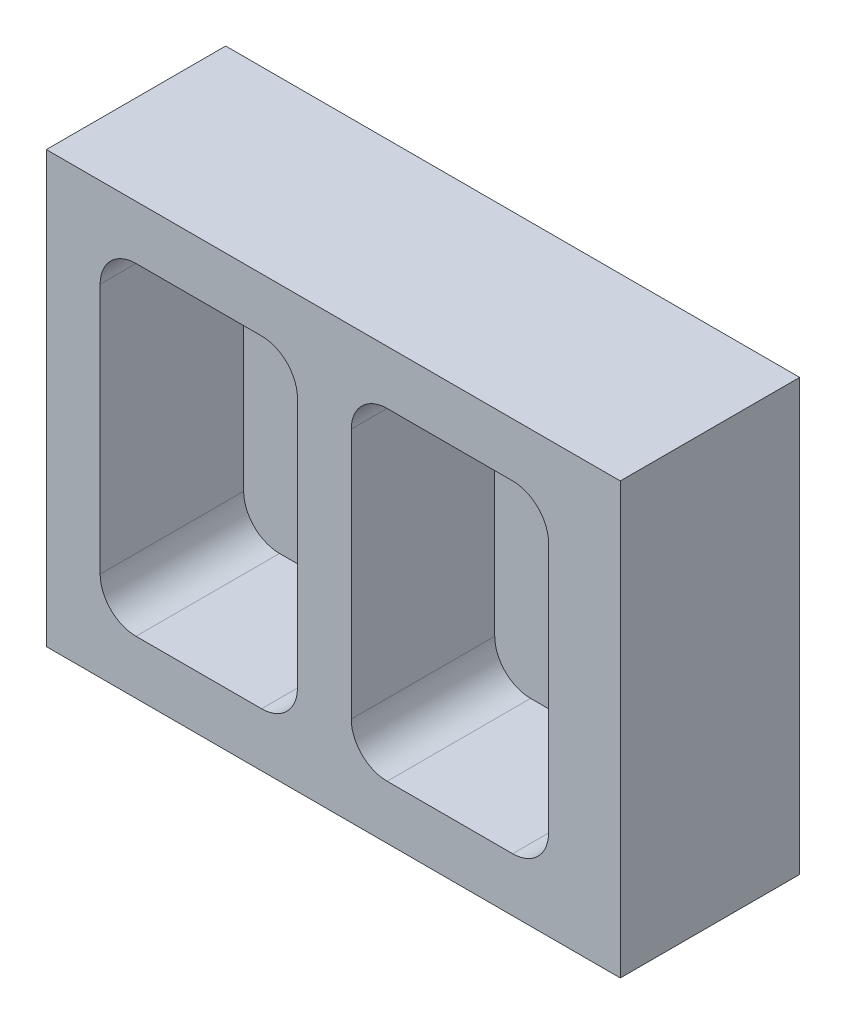
SolidWorks part; units mm, degrees
ref_plane "Plane1" through (0, 0, 0) normal (0, 0, 1) x (1, 0, 0)
ref_plane "Plane2" through (0, 0, 0) normal (0, 1, 0) x (1, 0, 0)
ref_plane "Plane3" through (0, 0, 0) normal (1, 0, 0) x (0, 0, -1)
sketch "Sketch1" plane through (0, 0, 0) normal (0, 0, 1) x (1, 0, 0)
  line L1 (-101.6, 76.2) -> (101.6, 76.2)
  line L2 (-101.6, 76.2) -> (-101.6, -76.2)
  line L3 (-101.6, -76.2) -> (101.6, -76.2)
  line L4 (101.6, 76.2) -> (101.6, -76.2)
extrude "Base-Extrude" add sketch "Sketch1" against normal blind 63.5
sketch "Sketch2" plane through (0, 0, 0) normal (0, 0, 1) x (1, 0, 0)
  line L1 (-69.85, 57.15) -> (-25.4, 57.15)
  line L2 (-82.55, 44.45) -> (-82.55, -44.45)
  line L3 (-69.85, -57.15) -> (-25.4, -57.15)
  line L4 (-12.7, 44.45) -> (-12.7, -44.45)
  line L5 (19.05, 57.15) -> (63.5, 57.15)
  line L6 (6.35, 44.45) -> (6.35, -44.45)
  line L7 (19.05, -57.15) -> (63.5, -57.15)
  line L8 (76.2, 44.45) -> (76.2, -44.45)
  arc A0 (-82.55, 44.45) -> (-69.85, 57.15) centre (-69.85, 44.45) cw
  arc A1 (-12.7, 44.45) -> (-25.4, 57.15) centre (-25.4, 44.45) ccw
  arc A2 (-12.7, -44.45) -> (-25.4, -57.15) centre (-25.4, -44.45) cw
  arc A3 (-69.85, -57.15) -> (-82.55, -44.45) centre (-69.85, -44.45) cw
  arc A4 (19.05, -57.15) -> (6.35, -44.45) centre (19.05, -44.45) cw
  arc A5 (76.2, -44.45) -> (63.5, -57.15) centre (63.5, -44.45) cw
  arc A6 (76.2, 44.45) -> (63.5, 57.15) centre (63.5, 44.45) ccw
  arc A7 (6.35, 44.45) -> (19.05, 57.15) centre (19.05, 44.45) cw
  point P10 (-82.55, 57.15)
  point P13 (-12.7, 57.15)
  point P18 (-82.55, -57.15)
  dimension "D3" = 12.7
  dimension "D1" = 69.85
  dimension "D2" = 114.3
  dimension "D4" = 69.85
  dimension "D5" = 114.3
extrude "Cut-Extrude1" cut sketch "Sketch2" against normal blind 50.8
